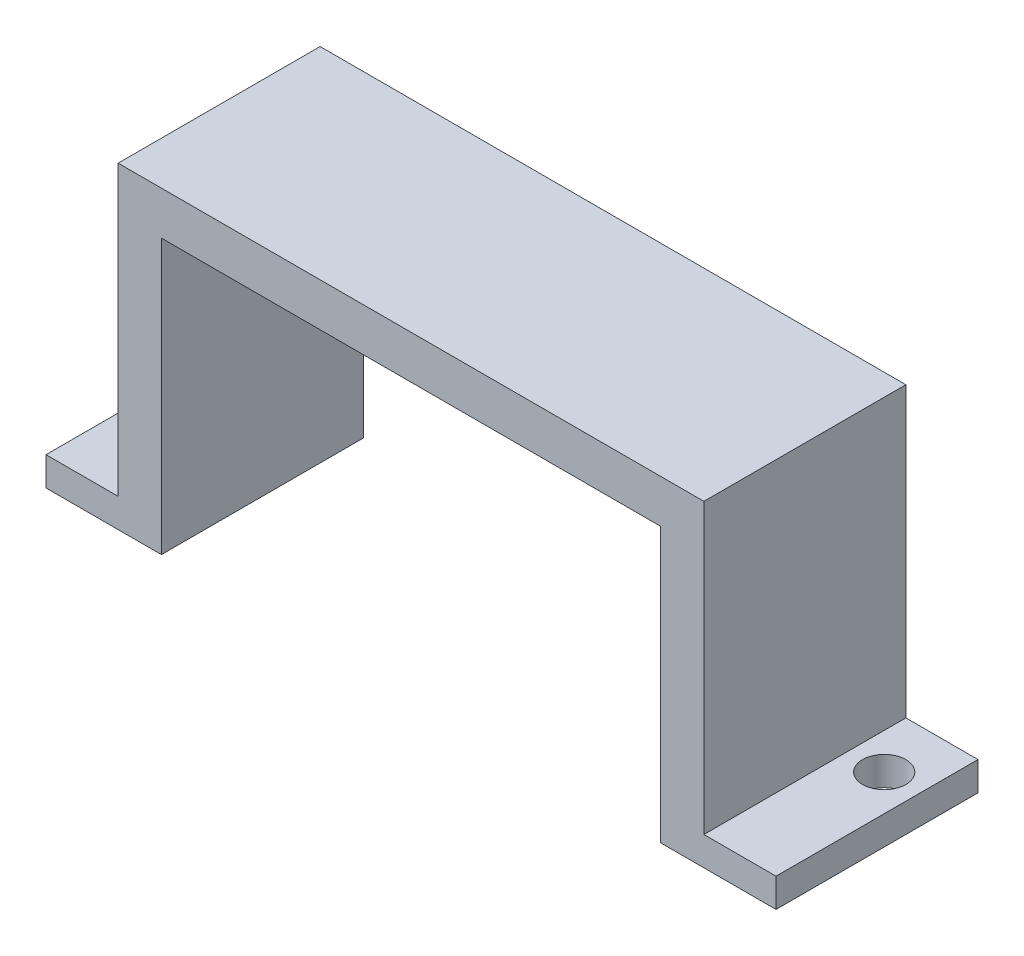
SolidWorks part; units mm, degrees
ref_plane "Front Plane" through (0, 0, 0) normal (0, 0, 1) x (1, 0, 0)
ref_plane "Top Plane" through (0, 0, 0) normal (0, 1, 0) x (1, 0, 0)
ref_plane "Right Plane" through (0, 0, 0) normal (1, 0, 0) x (0, 0, -1)
sketch "Sketch2" plane through (0, 0, 0) normal (0, 0, 1) x (1, 0, 0)
  line L1 (-25.67, -3.38) -> (8.93, -3.38)
  line L2 (-25.67, -3.38) -> (-25.67, 15.62)
  line L3 (-25.67, 15.62) -> (8.93, 15.62)
  line L4 (8.93, -3.38) -> (8.93, 15.62)
  line L5 (11.93, -1.38) -> (11.93, 18.62)
  line L6 (-28.67, 18.62) -> (11.93, 18.62)
  line L7 (-28.67, -1.38) -> (-28.67, 18.62)
  line L8 (-25.67, -3.38) -> (-12.23, -3.38)
  line L9 (8.93, -3.38) -> (11.93, -3.38)
  line L10 (-28.67, -6.38) -> (-28.67, 18.62) construction
  line L11 (-28.67, -6.38) -> (11.93, -6.38) construction
  line L12 (11.93, -6.38) -> (11.93, 18.62) construction
  line L14 (-12.23, -3.38) -> (-33.67, -3.38)
  line L16 (-28.67, -1.38) -> (-33.67, -1.38)
  line L17 (-33.67, -3.38) -> (-33.67, -1.38)
  line L18 (11.93, -3.38) -> (16.93, -3.38)
  line L20 (11.93, -1.38) -> (16.93, -1.38)
  line L21 (16.93, -3.38) -> (16.93, -1.38)
  point P0 (0, 0)
  dimension "D1" = 34.6
  dimension "D2" = 19
  dimension "D4" = 2
  dimension "D5" = 5
  dimension "D6" = 2
  dimension "D7" = 5
  dimension "D3" = 3
extrude "Boss-Extrude1" add sketch "Sketch2" along normal blind 14 contours L18 L21 L20 L5 L6 L7 L16 L17 L14 L8 L2 L3 L4 L9
sketch "Sketch3" plane through (0, -1.38, 0) normal (0, 1, 0) x (1, 0, 0)
  line L0 (11.93, 0) -> (16.93, 0) construction
  line L1 (11.93, -14) -> (11.93, 0) construction
  line L2 (-28.67, 0) -> (-33.67, 0) construction
  line L3 (-28.67, -14) -> (-28.67, 0) construction
  circle A0 centre (14.43, -4) radius 1.9118
  circle A1 centre (-31.17, -4) radius 1.7839
  dimension "D1" = 4
  dimension "D2" = 2.5
  dimension "D3" = 4
  dimension "D4" = 2.5
hole_wizard "Ø3.0 (3) Diameter Hole1" positions "Sketch4" profile "Sketch6" hole size "Ø3.0" standard "ANSI Metric" end condition through all
sketch "Sketch4" plane through (0, -1.38, 0) normal (0, 1, 0) x (1, 0, 0)
  point P0 (14.43, -4)
  point P4 (-31.17, -4)
sketch "Sketch6" plane through (14.43, -1.38, 4) normal (1, 0, 0) x (0, 0, 1)
  line L0 (0, 0) -> (0, 2)
  line L1 (0, 2) -> (1.5, 2)
  line L2 (1.5, 2) -> (1.5, 0)
  line L5 (1.5, 0) -> (0, 0)
  line L11 (0, -6.35) -> (0, 107.95) construction
  dimension "Thru Hole Dia." = 3
  dimension "Thru Hole Depth" = 2
